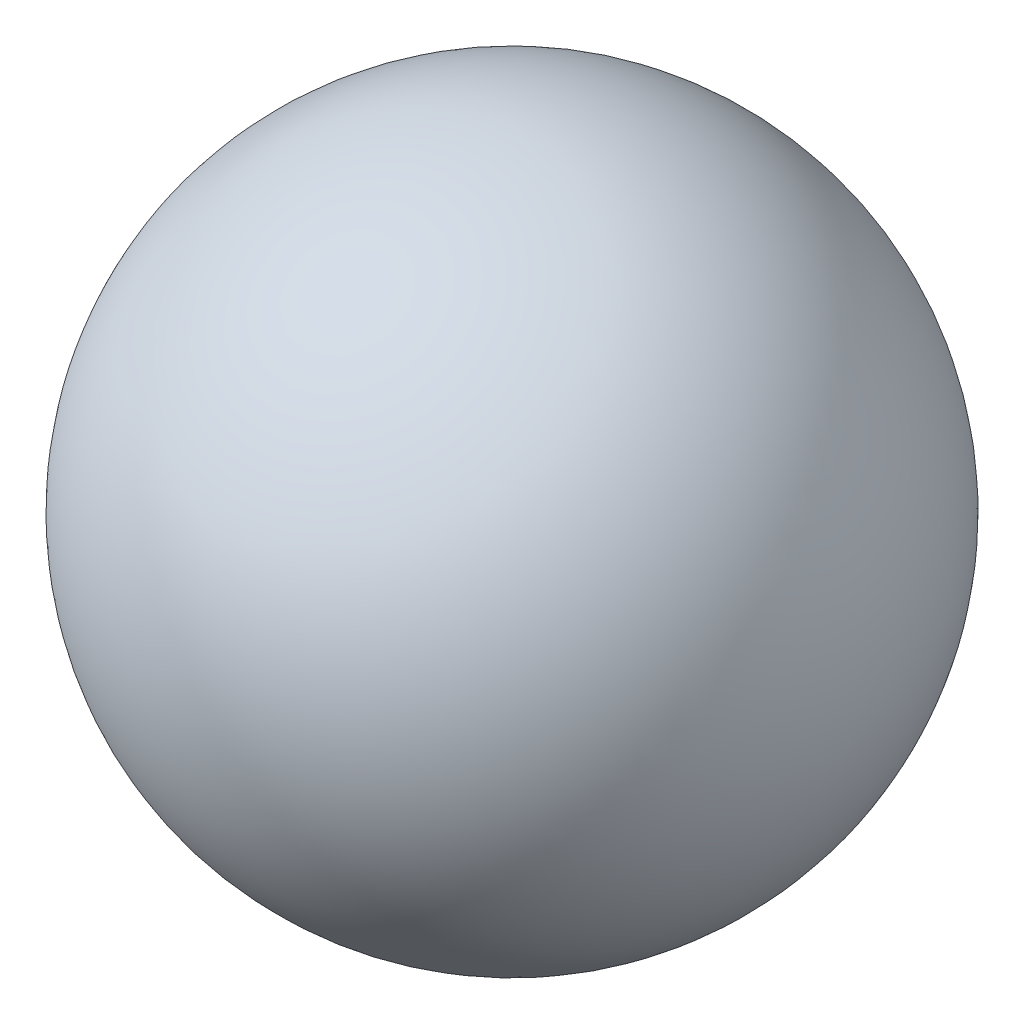
SolidWorks part; units mm, degrees
ref_plane "Front Plane" through (0, 0, 0) normal (0, 0, 1) x (1, 0, 0)
ref_plane "Top Plane" through (0, 0, 0) normal (0, 1, 0) x (1, 0, 0)
ref_plane "Right Plane" through (0, 0, 0) normal (1, 0, 0) x (0, 0, -1)
sketch "Sketch1" plane through (0, 0, 0) normal (0, 1, 0) x (1, 0, 0)
  line L0 (-2.25, 0) -> (2.25, 0)
  arc A0 (-2.25, 0) -> (2.25, 0) centre (0, 0) ccw
  dimension "D1" = 4.5
revolve "Revolve2" add sketch "Sketch1" angle 360 about L0
